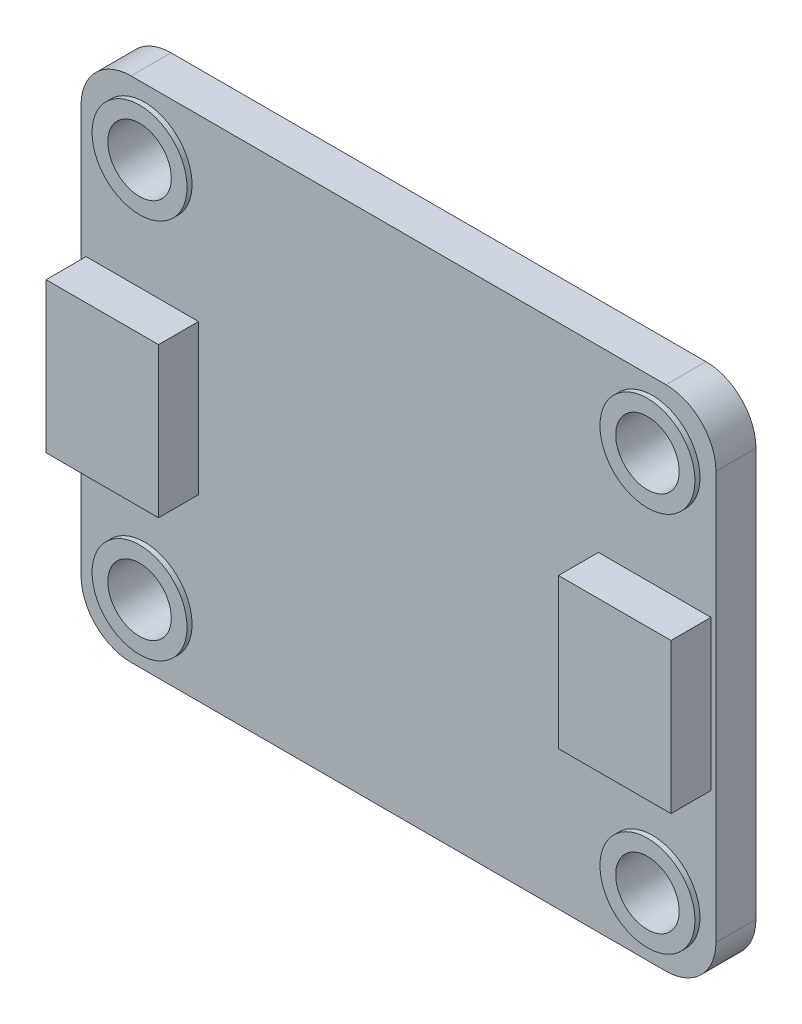
SolidWorks part; units mm, degrees
ref_plane "Front Plane" through (0, 0, 0) normal (0, 0, 1) x (1, 0, 0)
ref_plane "Top Plane" through (0, 0, 0) normal (0, 1, 0) x (1, 0, 0)
ref_plane "Right Plane" through (0, 0, 0) normal (1, 0, 0) x (0, 0, -1)
sketch "Sketch1" plane through (0, 0, 0) normal (0, 0, 1) x (1, 0, 0)
  line L1 (0, 0) -> (25.4, 0)
  line L2 (0, 0) -> (0, 20.32)
  line L3 (0, 20.32) -> (25.4, 20.32)
  line L4 (25.4, 0) -> (25.4, 20.32)
  dimension "D1" = 25.4
  dimension "D2" = 20.32
extrude "Boss-Extrude1" add sketch "Sketch1" along normal blind 1.6
fillet "Fillet1" radius 2 4 edges at (0, 20.32, 0.8) (0, 0, 0.8) (25.4, 0, 0.8) (25.4, 20.32, 0.8)
sketch "Sketch2" plane through (0, 0, 0) normal (0, 0, 1) x (1, 0, 0)
  line L0 (-2.0152, 10.16) -> (28.0497, 10.16) construction
  line L1 (23.4, 20.32) -> (2, 20.32) construction
  line L2 (12.7, 20.8716) -> (12.7, -1.8508) construction
  line L3 (25.4, 2) -> (25.4, 18.32) construction
  circle A0 centre (2.54, 17.78) radius 1.27
  circle A1 centre (22.86, 17.78) radius 1.27
  circle A2 centre (22.86, 2.54) radius 1.27
  circle A3 centre (2.54, 2.54) radius 1.27
  dimension "D1" = 2.54
  dimension "D2" = 10.16
  dimension "D3" = 7.62
  dimension "D4" = 7.62
  dimension "D5" = 12.7
  dimension "D6" = 10.16
  dimension "D7" = 10.16
extrude "Cut-Extrude1" cut sketch "Sketch2" along normal through all
sketch "Sketch5" plane through (0, 0, 0) normal (0, 0, 1) x (1, 0, 0)
  circle A0 centre (2.54, 17.78) radius 1.9
  circle A1 centre (22.86, 17.78) radius 1.9
  circle A2 centre (22.86, 2.54) radius 1.9
  circle A3 centre (2.54, 2.54) radius 1.9
  circle A4 centre (2.54, 2.54) radius 1.27
  circle A5 centre (2.54, 17.78) radius 1.27
  circle A6 centre (22.86, 17.78) radius 1.27
  circle A7 centre (22.86, 2.54) radius 1.27
  dimension "D1" = 3.8
  dimension "D2" = 2.54
extrude "Boss-Extrude4" add sketch "Sketch5" along normal blind 2 from offset 0.2 offset against normal yes
sketch "Sketch4" plane through (0, 0, 0) normal (0, 0, 1) x (1, 0, 0)
  line L0 (-2.7117, 10.16) -> (29.802, 10.16) construction
  line L1 (0.88, 0) -> (-0.88, 0) construction
  line L2 (0, -0.88) -> (0, 0.88) construction
  line L3 (0.2, 13.16) -> (4.7, 13.16)
  line L4 (0.2, 13.16) -> (0.2, 7.16)
  line L5 (0.2, 7.16) -> (4.7, 7.16)
  line L6 (4.7, 13.16) -> (4.7, 7.16)
  line L7 (20.7, 13.16) -> (25.2, 13.16)
  line L8 (20.7, 13.16) -> (20.7, 7.16)
  line L9 (20.7, 7.16) -> (25.2, 7.16)
  line L10 (25.2, 13.16) -> (25.2, 7.16)
  line L11 (25.4, 2) -> (25.4, 18.32) construction
  dimension "D1" = 10.16
  dimension "D2" = 4.5
  dimension "D3" = 4.5
  dimension "D4" = 6
  dimension "D5" = 6
  dimension "D6" = 3
  dimension "D7" = 3
  dimension "D8" = 0.2
  dimension "D9" = 0.2
extrude "Boss-Extrude3" add sketch "Sketch4" along normal blind 1.6 from surface at 1.6 starting at face at (20.96, 2.54, 1.6)
